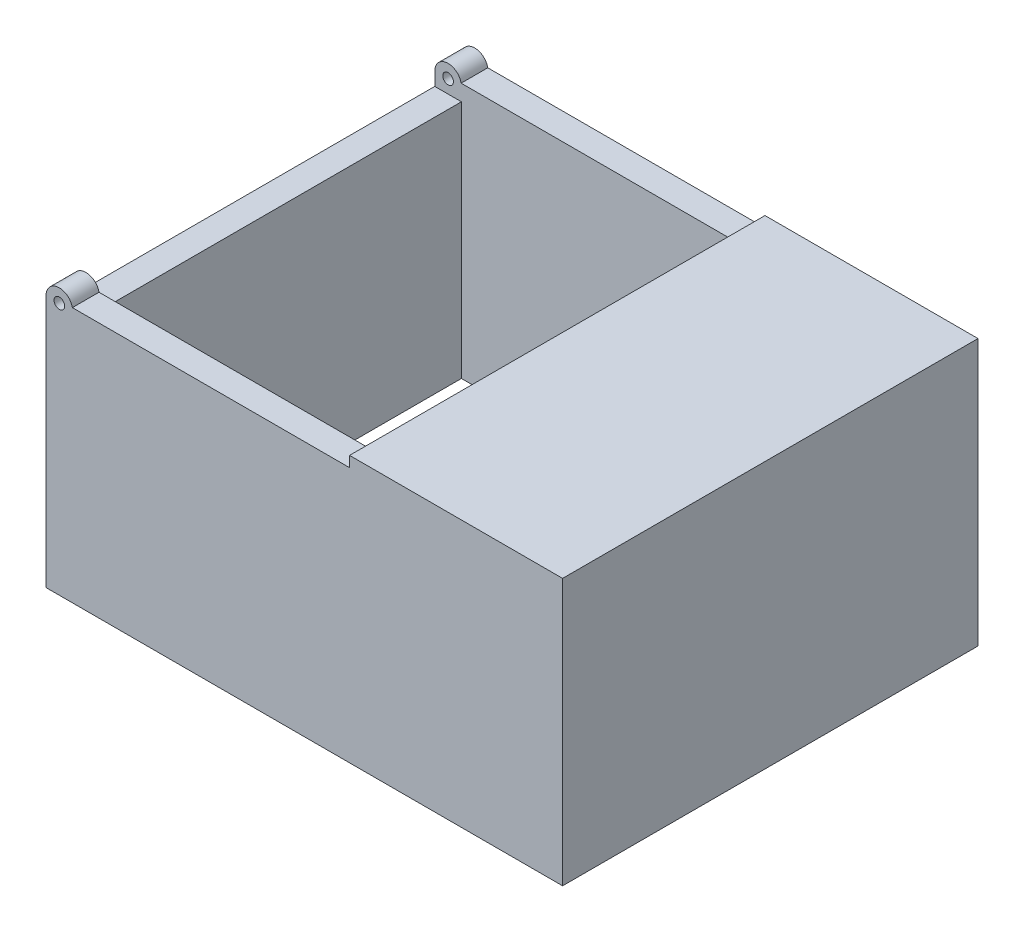
SolidWorks part; units mm, degrees
ref_plane "Front Plane" through (0, 0, 0) normal (0, 0, 1) x (1, 0, 0)
ref_plane "Top Plane" through (0, 0, 0) normal (0, 1, 0) x (1, 0, 0)
ref_plane "Right Plane" through (0, 0, 0) normal (1, 0, 0) x (0, 0, -1)
sketch "Sketch1" plane through (0, 0, 0) normal (0, 0, 1) x (1, 0, 0)
  line L1 (-97, -50) -> (97, -50)
  line L2 (-97, -50) -> (-97, 50)
  line L3 (-97, 50) -> (97, 50)
  line L4 (97, -50) -> (97, 50)
  line L7 (97, 50) -> (17, 50)
  line L8 (97, 50) -> (97, 45)
  line L9 (97, 45) -> (17, 45)
  line L10 (17, 50) -> (17, 45)
extrude "Boss-Extrude1" add sketch "Sketch1" along normal blind 156 contours L10 L3 L2 L1 L4 L9 | L3 L10 L9 L4
sketch "Sketch2" plane through (0, -50, 0) normal (0, -1, 0) x (-1, 0, 0)
  line L1 (97, 0) -> (-97, 0)
  line L2 (97, 0) -> (97, -156)
  line L3 (97, -156) -> (-97, -156)
  line L4 (-97, 0) -> (-97, -156)
  line L5 (87, -10) -> (-87, -10)
  line L6 (87, -10) -> (87, -146)
  line L7 (87, -146) -> (-87, -146)
  line L8 (-87, -10) -> (-87, -146)
extrude "Cut-Extrude1" cut sketch "Sketch2" against normal blind 96 contours L6 L5 L8 L7
sketch "Sketch3" plane through (0, 50, 0) normal (0, 1, 0) x (1, 0, 0)
  line L1 (-87, -146) -> (87, -146)
  line L2 (-87, -146) -> (-87, -10)
  line L3 (-87, -10) -> (87, -10)
  line L4 (87, -146) -> (87, -10)
  line L5 (87, -10) -> (7, -10)
  line L6 (87, -10) -> (87, -146)
  line L7 (87, -146) -> (7, -146)
  line L8 (7, -10) -> (7, -146)
extrude "Cut-Extrude2" cut sketch "Sketch3" against normal blind 96 contours L8 L3 L2 L1
sketch "Sketch6" plane through (0, 0, 10) normal (0, 0, 1) x (1, 0, 0)
  line L1 (7, 50) -> (17, 50)
  line L2 (7, 50) -> (7, 45)
  line L3 (7, 45) -> (17, 45)
  line L4 (17, 50) -> (17, 45)
extrude "Cut-Extrude3" cut sketch "Sketch6" along normal up to surface (136 mm away) up to face at (2.3333, 15.3333, 146)
sketch "Sketch7" plane through (0, 0, 10) normal (0, 0, 1) x (1, 0, 0)
  line L0 (-97, -50) -> (-97, 50) construction
  line L1 (17, 50) -> (-97, 50)
  line L2 (17, 50) -> (17, 46)
  line L3 (17, 46) -> (-97, 46)
  line L4 (-97, 50) -> (-97, 46)
extrude "Cut-Extrude4" cut sketch "Sketch7" against normal through all both and the other way through all
sketch "Sketch8" plane through (0, 0, 0) normal (0, 0, 1) x (1, 0, 0)
  line L0 (17, 50) -> (-97, 50)
  line L1 (-97, 46) -> (-97, 50)
  line L2 (-97, 45) -> (-97, 46)
  line L3 (-92, 40) -> (-97, 40)
  line L4 (-97, -50) -> (-97, 46) construction
  line L5 (-97, 40) -> (-97, 50)
  line L6 (-92, 40) -> (-87, 40)
  line L7 (-87, 46) -> (-87, -50) construction
  line L10 (17, 46) -> (17, 50)
  line L11 (-87, 40) -> (-87, 46)
  line L12 (-87, 46) -> (-97, 46)
extrude "Cut-Extrude9" cut sketch "Sketch8" along normal up to surface (156 mm away) contours L11 L12 L2 L5 L3 L6 up to face at (5.6667, 15.3333, 156)
sketch "Sketch9" plane through (0, 0, 156) normal (0, 0, 1) x (1, 0, 0)
  line L0 (-97, 40) -> (-97, 45)
  line L1 (-97, 40) -> (-87, 40)
  line L2 (-87, 40) -> (-87, 45)
  line L3 (-87, 46) -> (-87.101, 46)
  line L4 (-87, 46) -> (-87, 45)
  arc A1 (-87.101, 46) -> (-97, 45) centre (-92, 45) ccw
extrude "Boss-Extrude2" add sketch "Sketch9" against normal blind 10
sketch "Sketch10" plane through (0, 0, 146) normal (0, 0, -1) x (-1, 0, 0)
  circle A0 centre (92, 45) radius 2
extrude "Cut-Extrude10" cut sketch "Sketch10" against normal blind 96
ref_plane "Plane1" through (0, 0, 78) normal (0, 0, 1) x (1, 0, 0)
mirror "Mirror1" about plane through (0, 0, 78) normal (0, 0, 1) of "Cut-Extrude10", "Boss-Extrude2"
sketch "Sketch11" plane through (0, 0, 156) normal (0, 0, 1) x (1, 0, 0)
  line L0 (-92, 45) -> (-92, 50)
  line L1 (-87.101, 46) -> (-92, 46)
  arc A0 (-87.101, 46) -> (-97, 45) centre (-92, 45) ccw construction
sketch "Sketch12" plane through (0, -50, 0) normal (0, -1, 0) x (-1, 0, 0)
  line L2 (-97, -156) -> (-97, 0)
  line L3 (-97, 0) -> (97, 0)
  circle A5 centre (92, -5) radius 2
  circle A6 centre (92, -151) radius 2
  circle A7 centre (-92, -151) radius 2
  circle A8 centre (-92, -5) radius 2
extrude "Cut-Extrude11" cut sketch "Sketch12" against normal blind 60 contours A6 | A7 | A8 | A5
